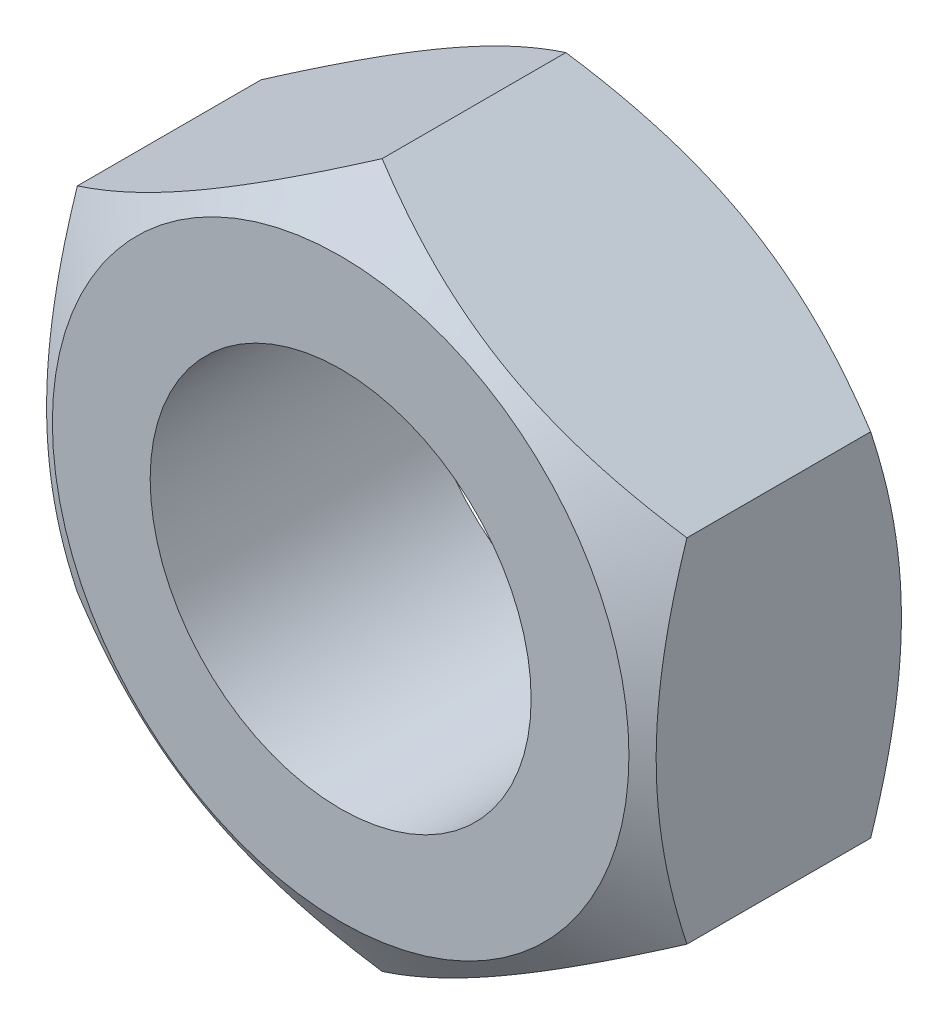
SolidWorks part; units mm, degrees
ref_plane "前视基准面" through (0, 0, 0) normal (0, 0, 1) x (1, 0, 0)
ref_plane "上视基准面" through (0, 0, 0) normal (0, 1, 0) x (1, 0, 0)
ref_plane "右视基准面" through (0, 0, 0) normal (1, 0, 0) x (0, 0, -1)
sketch "草图1" plane through (0, 0, 0) normal (0, 0, 1) x (1, 0, 0)
  line L1 (0, 3.695) -> (-3.2, 1.8475)
  line L2 (-3.2, 1.8475) -> (-3.2, -1.8475)
  line L3 (-3.2, -1.8475) -> (0, -3.695)
  line L4 (0, -3.695) -> (3.2, -1.8475)
  line L5 (3.2, -1.8475) -> (3.2, 1.8475)
  line L6 (3.2, 1.8475) -> (0, 3.695)
  circle A0 centre (0, 0) radius 2
  circle A1 centre (0, 0) radius 3.2 construction
extrude "凸台-拉伸1" add sketch "草图1" along normal blind 2.8
ref_plane "基准面1" through (0, 0, 1.4) normal (0, 0, -1) x (-1, 0, 0)
ref_axis "基准轴1" through (0, 0, 2.8) along (0, 0, -1)
sketch "草图2" plane through (0, 0, 0) normal (1, 0, 0) x (0, 0, -1)
  line L0 (-2.3646, 3.695) -> (-2.8, 3.0268)
  line L1 (-2.8, 3.695) -> (0, 3.695) construction
  line L2 (-2.8, 1.8475) -> (-2.8, 3.695) construction
  line L3 (-2.8, 3.0268) -> (-2.8, 3.695)
  line L4 (-2.8, 3.695) -> (-2.3646, 3.695)
revolve "切除-旋转1" cut sketch "草图2" angle 360 about axis through (0, 0, 2.8) along (0, 0, -1)
mirror "镜向1" about plane through (0, 0, 1.4) normal (0, 0, -1) of "切除-旋转1"
